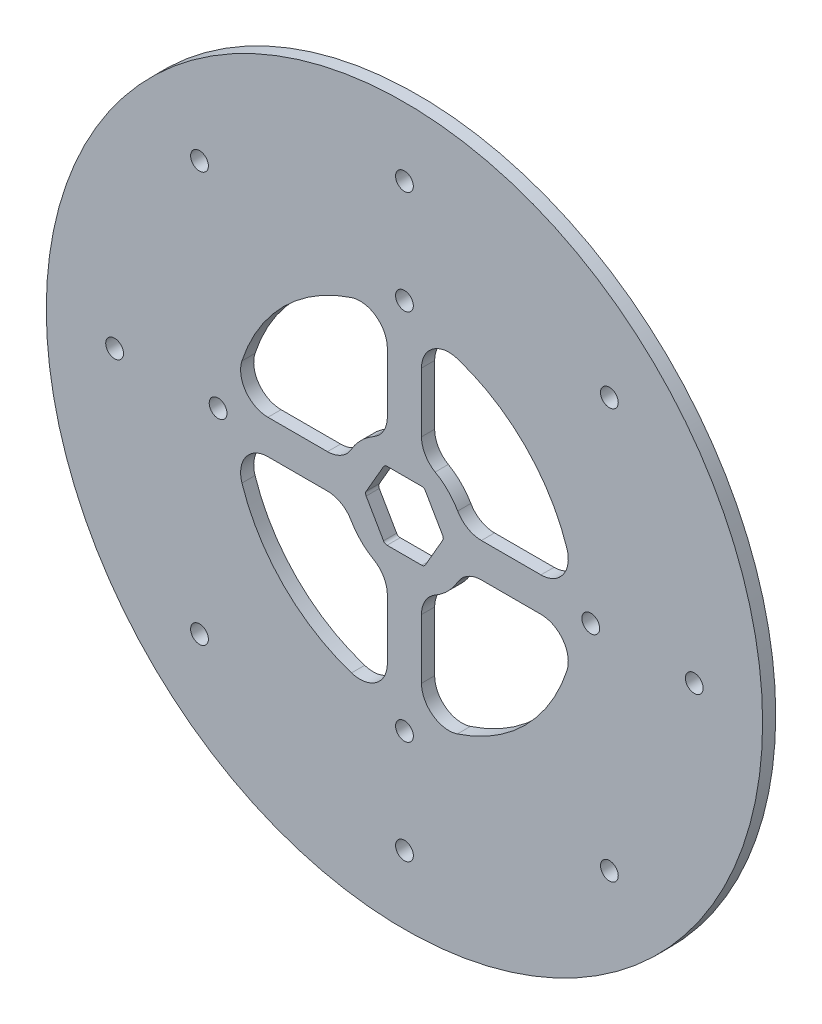
SolidWorks part; units mm, degrees
material "Stainless Steel (ferritic)"
ref_plane "Front Plane" through (0, 0, 0) normal (0, 0, 1) x (1, 0, 0)
ref_plane "Top Plane" through (0, 0, 0) normal (0, 1, 0) x (1, 0, 0)
ref_plane "Right Plane" through (0, 0, 0) normal (1, 0, 0) x (0, 0, -1)
sketch "Sketch1" plane through (0, 0, 0) normal (0, 0, 1) x (1, 0, 0)
  line L0 (0, 0) -> (112.8361, 0) construction
  line L1 (0, -1000) -> (0, 49000) construction
  line L2 (25.3603, 3.175) -> (14.2981, 3.175)
  line L3 (3.175, 25.3603) -> (3.175, 14.2981)
  line L4 (-3.175, 25.3603) -> (-3.175, 14.2981)
  line L5 (3.175, -25.3603) -> (3.175, -14.2981)
  line L7 (-25.3603, 3.175) -> (-14.2981, 3.175)
  line L8 (25.3603, -3.175) -> (14.2981, -3.175)
  line L9 (7.3323, 0) -> (3.6662, 6.35)
  line L10 (-25.3603, -3.175) -> (-14.2981, -3.175)
  line L11 (-3.175, -25.3603) -> (-3.175, -14.2981)
  line L12 (3.6662, 6.35) -> (-3.6662, 6.35)
  line L13 (-3.6662, 6.35) -> (-7.3323, 0)
  line L14 (-7.3323, 0) -> (-3.6662, -6.35)
  line L15 (-3.6662, -6.35) -> (3.6662, -6.35)
  line L16 (3.6662, -6.35) -> (7.3323, 0)
  circle A0 centre (0, 0) radius 66.548
  circle A1 centre (0, 0) radius 11.43 construction
  arc A2 (-31.5909, -3.175) -> (3.175, 31.5909) centre (0, 0) ccw construction
  arc A3 (-10.9802, -3.175) -> (3.175, 10.9802) centre (0, 0) ccw construction
  arc A5 (-5.715, 9.8987) -> (-9.8987, 5.715) centre (0, 0) ccw
  arc A6 (-9.8274, 30.1908) -> (-30.1908, 9.8274) centre (0, 0) ccw
  arc A7 (-5.715, 9.8987) -> (-3.175, 14.2981) centre (-8.255, 14.2981) ccw
  arc A8 (-14.2981, 3.175) -> (-9.8987, 5.715) centre (-14.2981, 8.255) ccw
  arc A9 (-9.8274, 30.1908) -> (-3.175, 25.3603) centre (-8.255, 25.3603) cw
  arc A10 (-30.1908, 9.8274) -> (-25.3603, 3.175) centre (-25.3603, 8.255) ccw
  arc A11 (9.8987, 5.715) -> (5.715, 9.8987) centre (0, 0) ccw
  arc A12 (30.1908, 9.8274) -> (9.8274, 30.1908) centre (0, 0) ccw
  arc A13 (9.8987, 5.715) -> (14.2981, 3.175) centre (14.2981, 8.255) ccw
  arc A14 (3.175, 14.2981) -> (5.715, 9.8987) centre (8.255, 14.2981) ccw
  arc A15 (30.1908, 9.8274) -> (25.3603, 3.175) centre (25.3603, 8.255) cw
  arc A16 (9.8274, 30.1908) -> (3.175, 25.3603) centre (8.255, 25.3603) ccw
  arc A17 (5.715, -9.8987) -> (9.8987, -5.715) centre (0, 0) ccw
  arc A18 (9.8274, -30.1908) -> (30.1908, -9.8274) centre (0, 0) ccw
  arc A19 (5.715, -9.8987) -> (3.175, -14.2981) centre (8.255, -14.2981) ccw
  arc A20 (14.2981, -3.175) -> (9.8987, -5.715) centre (14.2981, -8.255) ccw
  arc A21 (9.8274, -30.1908) -> (3.175, -25.3603) centre (8.255, -25.3603) cw
  arc A22 (30.1908, -9.8274) -> (25.3603, -3.175) centre (25.3603, -8.255) ccw
  arc A23 (-9.8987, -5.715) -> (-5.715, -9.8987) centre (0, 0) ccw
  arc A24 (-30.1908, -9.8274) -> (-9.8274, -30.1908) centre (0, 0) ccw
  arc A25 (-9.8987, -5.715) -> (-14.2981, -3.175) centre (-14.2981, -8.255) ccw
  arc A26 (-3.175, -14.2981) -> (-5.715, -9.8987) centre (-8.255, -14.2981) ccw
  arc A27 (-30.1908, -9.8274) -> (-25.3603, -3.175) centre (-25.3603, -8.255) cw
  arc A28 (-9.8274, -30.1908) -> (-3.175, -25.3603) centre (-8.255, -25.3603) ccw
  circle A29 centre (0, 53.848) radius 1.651
  circle A30 centre (0, 34.6196) radius 1.651
  circle A31 centre (0, 0) radius 6.35 construction
  circle A32 centre (34.6196, 0) radius 1.651
  circle A34 centre (0, -34.6196) radius 1.651
  circle A36 centre (-34.6196, 0) radius 1.651
  circle A39 centre (38.0763, 38.0763) radius 1.651
  circle A40 centre (0, 0) radius 53.848 construction
  circle A41 centre (53.848, 0) radius 1.651
  circle A42 centre (38.0763, -38.0763) radius 1.651
  circle A43 centre (0, -53.848) radius 1.651
  circle A44 centre (-38.0763, -38.0763) radius 1.651
  circle A45 centre (-53.848, 0) radius 1.651
  circle A46 centre (-38.0763, 38.0763) radius 1.651
  circle A47 centre (-53.848, 0) radius 1.651 [skipped]
  circle A48 centre (0, -53.848) radius 1.651 [skipped]
  circle A49 centre (53.848, 0) radius 1.651 [skipped]
  point P15 (-3.175, 10.9802)
  point P23 (-10.9802, 3.175)
  point P26 (-3.175, 31.5909)
  point P68 (0, 0)
  point P85 (0, 0)
  point P108 (0, 0)
  dimension "D1" = 63.5
  dimension "D6" = 5.08
  dimension "D7" = 5.08
  dimension "D9" = 4
  dimension "D10" = 12.7
  dimension "D11" = 133.096
  dimension "D13" = 3.302
  dimension "D14" = 3.302
  dimension "D15" = 12.7
  dimension "D4" = 6.35
  dimension "D5" = 6.35
  dimension "D8" = 4
  dimension "D12" = 8
extrude "Boss-Extrude1" add sketch "Sketch1" along normal blind 2.4384
fillet "Fillet6" radius 0.762 6 edges at (3.6662, 6.35, 1.2192) (7.3323, 0, 1.2192) (3.6662, -6.35, 1.2192) (-3.6662, -6.35, 1.2192) (-7.3323, 0, 1.2192) (-3.6662, 6.35, 1.2192)
